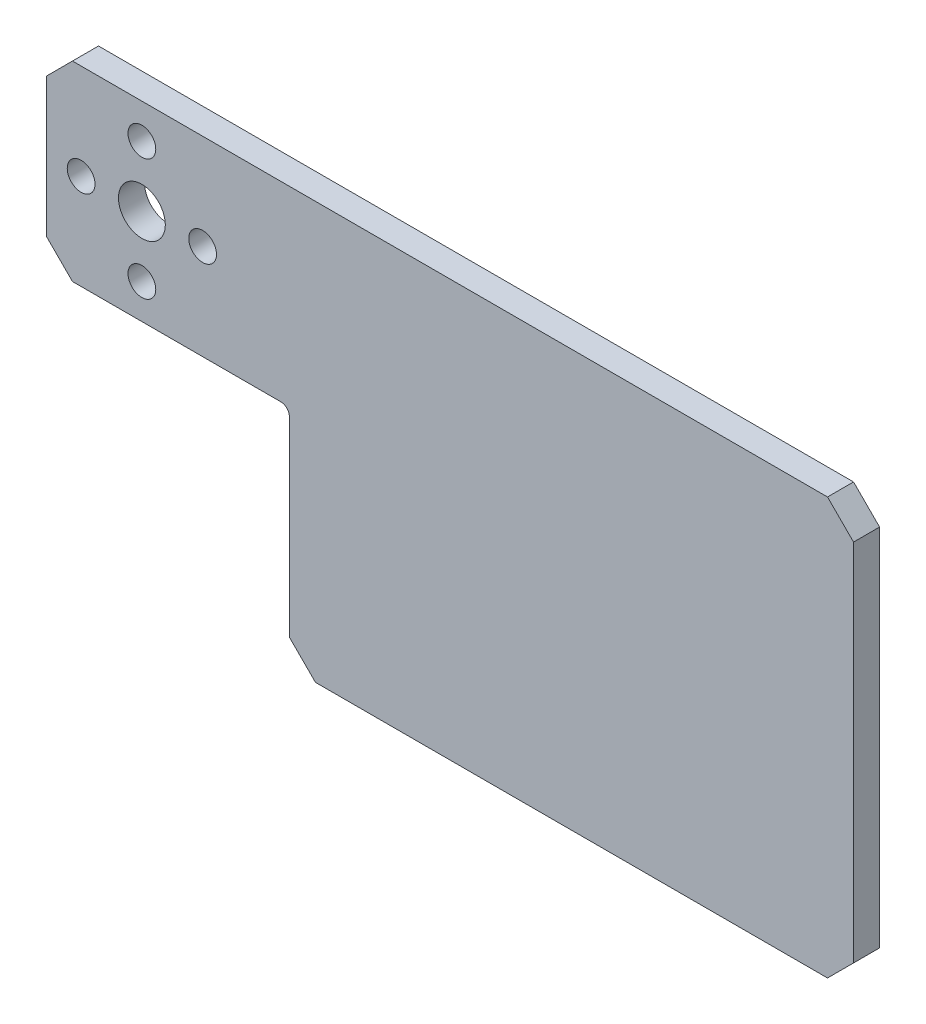
SolidWorks part; units mm, degrees
ref_plane "前基準面" through (0, 0, 0) normal (0, 0, 1) x (1, 0, 0)
ref_plane "上基準面" through (0, 0, 0) normal (0, 1, 0) x (1, 0, 0)
ref_plane "右基準面" through (0, 0, 0) normal (1, 0, 0) x (0, 0, -1)
sketch "草圖1" plane through (0, 0, 0) normal (0, 0, 1) x (1, 0, 0)
  line L1 (46.5, -24) -> (-46.5, -24)
  line L2 (46.5, -24) -> (46.5, 24)
  line L3 (46.5, 24) -> (-46.5, 24)
  line L4 (-46.5, -24) -> (-46.5, 24)
  line L5 (46.5, -24) -> (-46.5, 24) construction
  line L6 (46.5, 24) -> (-46.5, -24) construction
  point P0 (0, 0)
  dimension "D1" = 93
  dimension "D2" = 48
extrude "填料-伸長1" add sketch "草圖1" along normal blind 3
sketch "草圖2" plane through (0, 0, 3) normal (0, 0, 1) x (1, 0, 0)
  line L1 (46.5, 24) -> (-46.5, 24) construction
  line L2 (-35.5, 13) -> (-28.5, 13) construction
  line L3 (-46.5, 24) -> (-46.5, -24) construction
  circle A0 centre (-35.5, 13) radius 2.7
  circle A1 centre (-28.5, 13) radius 1.6
  dimension "D1" = 11
  dimension "D3" = 5.4
  dimension "D4" = 3.2
  dimension "D5" = 7
  dimension "D2" = 11
extrude "除料-伸長1" cut sketch "草圖2" against normal through all
pattern_circular "環狀複製排列1" count 4 over 360 about axis through (-35.5, 13, 0) along (0, 0, 1) of "除料-伸長1"
sketch "草圖3" plane through (0, 0, 3) normal (0, 0, 1) x (1, 0, 0)
  line L1 (-46.5, -24) -> (-18.5, -24)
  line L2 (-46.5, -24) -> (-46.5, 2)
  line L3 (-46.5, 2) -> (-18.5, 2)
  line L4 (-18.5, -24) -> (-18.5, 2)
  circle A0 centre (-35.5, 13) radius 2.7 construction
  dimension "D1" = 65
  dimension "D2" = 11
extrude "除料-伸長2" cut sketch "草圖3" against normal through all
fillet "圓角1" radius 1 1 edges at (-18.5, 2, 1.5)
chamfer "導角1" distance 3 angle 45 5 edges at (-18.5, -24, 1.5) (46.5, -24, 1.5) (46.5, 24, 1.5) (-46.5, 24, 1.5) (-46.5, 2, 1.5)
